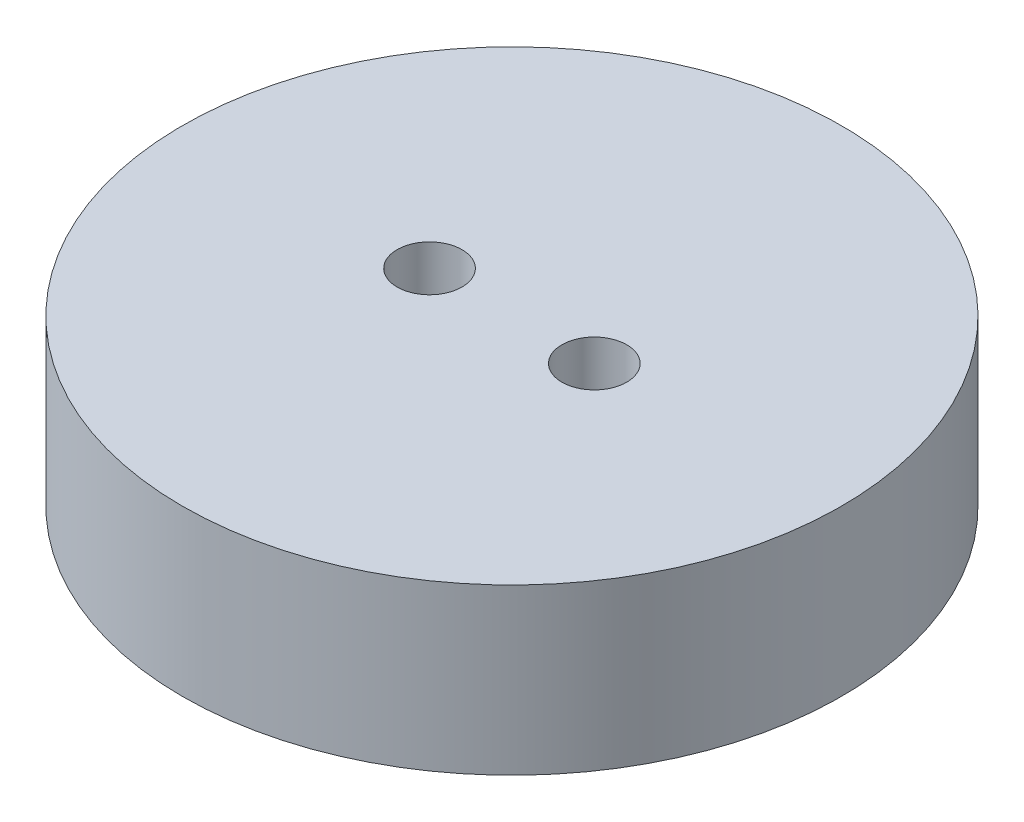
SolidWorks part; units mm, degrees
ref_plane "Front Plane" through (0, 0, 0) normal (0, 0, 1) x (1, 0, 0)
ref_plane "Top Plane" through (0, 0, 0) normal (0, 1, 0) x (1, 0, 0)
ref_plane "Right Plane" through (0, 0, 0) normal (1, 0, 0) x (0, 0, -1)
sketch "Sketch1" plane through (0, 0, 0) normal (0, 1, 0) x (1, 0, 0)
  circle A0 centre (0, 0) radius 25.4
  dimension "D1" = 50.8
extrude "Boss-Extrude1" add sketch "Sketch1" along normal blind 12.7 contours A0
sketch "Sketch2" plane through (0, 12.7, 0) normal (0, 1, 0) x (1, 0, 0)
  line L0 (0, 0) -> (6.35, 0)
  line L1 (-6.985, 0) -> (6.985, 0) construction
  line L2 (0, 0) -> (-6.35, 0)
  point P1 (6.35, 0)
  point P7 (-6.35, 0)
  dimension "D1" = 12.7
hole_wizard "M6x1.0 Tapped Hole1" positions "Sketch2" profile "Sketch3" tap size "M6x1.0" standard "ANSI Metric" end condition through all
sketch "Sketch3" plane through (-6.35, 12.7, 0) normal (1, 0, 0) x (0, 0, 1)
  line L0 (0, 0) -> (0, 12.7)
  line L1 (0, 12.7) -> (2.5, 12.7)
  line L2 (2.5, 12.7) -> (2.5, 0)
  line L5 (2.5, 0) -> (0, 0)
  line L11 (0, -6.35) -> (0, 107.95) construction
  dimension "Thru Tap Drill Dia." = 5
  dimension "Thru Tap Drill Depth" = 12.7
equation "\"liddiameter\"= 2in"
equation "\"lidheight\"= 0.5in"
equation "\"lidscrewholediff\"= 0.5in"
equation "\"D1@Sketch1\"=\"liddiameter\""
equation "\"D1@Boss-Extrude1\"=\"lidheight\""
equation "\"D1@Sketch2\"=\"lidscrewholediff\""
